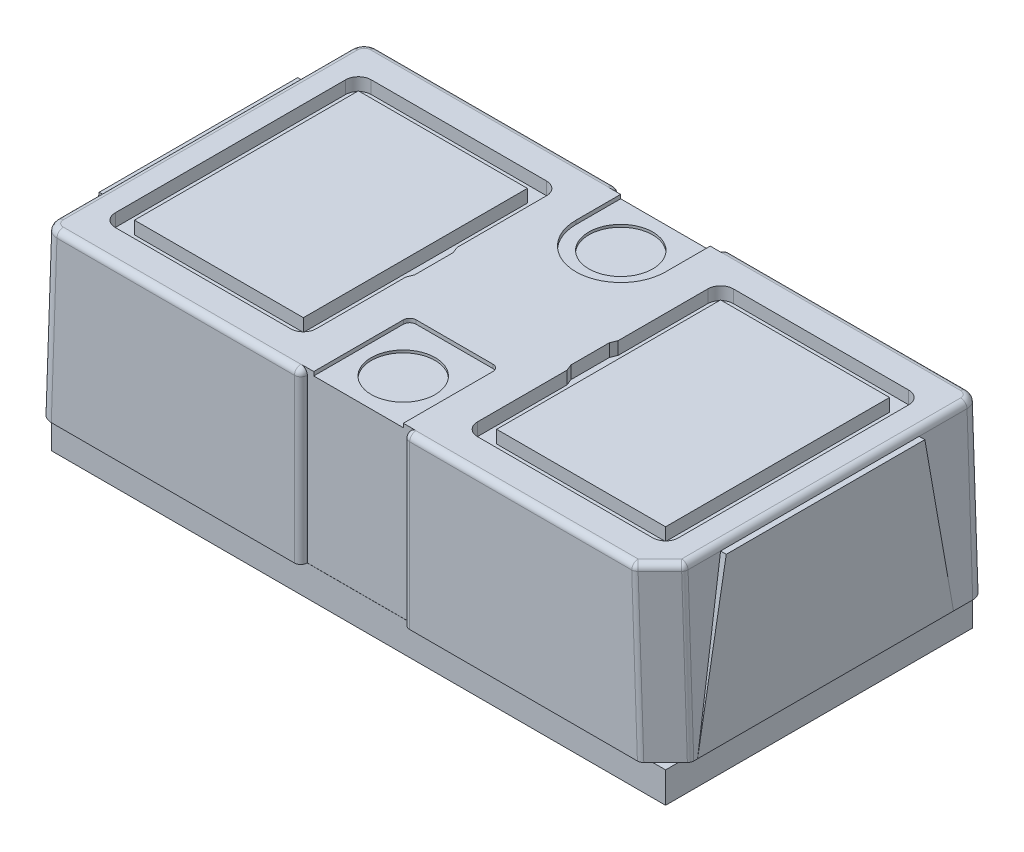
SolidWorks part; units mm, degrees
ref_plane "Front Plane" through (0, 0, 0) normal (0, 0, 1) x (1, 0, 0)
ref_plane "Top Plane" through (0, 0, 0) normal (0, 1, 0) x (1, 0, 0)
ref_plane "Right Plane" through (0, 0, 0) normal (1, 0, 0) x (0, 0, -1)
sketch "Sketch1" plane through (0, 0, 0) normal (0, 1, 0) x (1, 0, 0)
  line L1 (-2.4, -1.2) -> (2.4, -1.2)
  line L2 (-2.4, -1.2) -> (-2.4, 1.2)
  line L3 (-2.4, 1.2) -> (2.4, 1.2)
  line L4 (2.4, -1.2) -> (2.4, 1.2)
  line L5 (-2.4, -1.2) -> (2.4, 1.2) construction
  line L6 (-2.4, 1.2) -> (2.4, -1.2) construction
  point P0 (0, 0)
  dimension "D1" = 4.8
  dimension "D2" = 2.4
extrude "Boss-Extrude1" add sketch "Sketch1" along normal blind 0.24
sketch "Sketch2" plane through (0, 0, 0) normal (0, -1, 0) x (1, 0, 0)
  line L0 (-2.4, -1.2) -> (-2.4, 1.2) construction
  line L1 (-1.85, 1.05) -> (-1.35, 1.05)
  line L2 (-1.85, 1.05) -> (-1.85, 0.55)
  line L3 (-1.85, 0.55) -> (-1.35, 0.55)
  line L4 (-1.35, 1.05) -> (-1.35, 0.55)
  line L5 (-1.05, 1.05) -> (-0.55, 1.05)
  line L6 (-1.05, 1.05) -> (-1.05, 0.55)
  line L7 (-1.05, 0.55) -> (-0.55, 0.55)
  line L8 (-0.55, 1.05) -> (-0.55, 0.55)
  line L9 (-0.25, 1.05) -> (0.25, 1.05)
  line L10 (-0.25, 1.05) -> (-0.25, 0.55)
  line L11 (-0.25, 0.55) -> (0.25, 0.55)
  line L12 (0.25, 1.05) -> (0.25, 0.55)
  line L13 (0.55, 1.05) -> (1.05, 1.05)
  line L14 (0.55, 1.05) -> (0.55, 0.55)
  line L15 (0.55, 0.55) -> (1.05, 0.55)
  line L16 (1.05, 1.05) -> (1.05, 0.55)
  line L17 (1.35, 1.05) -> (1.85, 1.05)
  line L18 (1.35, 1.05) -> (1.35, 0.55)
  line L19 (1.35, 0.55) -> (1.85, 0.55)
  line L20 (1.85, 1.05) -> (1.85, 0.55)
  line L21 (-1.85, 0.25) -> (-1.35, 0.25)
  line L22 (-1.85, 0.25) -> (-1.85, -0.25)
  line L23 (-1.85, -0.25) -> (-1.35, -0.25)
  line L24 (-1.35, 0.25) -> (-1.35, -0.25)
  line L25 (-1.93, -0.55) -> (-1.35, -0.55)
  line L26 (-1.85, -0.8) -> (-1.85, -1.05)
  line L27 (-1.85, -1.05) -> (-1.35, -1.05)
  line L28 (-1.35, -0.55) -> (-1.35, -1.05)
  line L29 (-1.05, -0.55) -> (-0.55, -0.55)
  line L30 (-1.05, -0.55) -> (-1.05, -1.05)
  line L31 (-1.05, -1.05) -> (-0.55, -1.05)
  line L32 (-0.55, -0.55) -> (-0.55, -1.05)
  line L33 (-0.25, -0.55) -> (0.25, -0.55)
  line L34 (-0.25, -0.55) -> (-0.25, -1.05)
  line L35 (-0.25, -1.05) -> (0.25, -1.05)
  line L36 (0.25, -0.55) -> (0.25, -1.05)
  line L37 (0.55, -0.55) -> (1.05, -0.55)
  line L38 (0.55, -0.55) -> (0.55, -1.05)
  line L39 (0.55, -1.05) -> (1.05, -1.05)
  line L40 (1.05, -0.55) -> (1.05, -1.05)
  line L41 (1.35, -0.55) -> (1.85, -0.55)
  line L42 (1.35, -0.55) -> (1.35, -1.05)
  line L43 (1.35, -1.05) -> (1.85, -1.05)
  line L44 (1.85, -0.55) -> (1.85, -1.05)
  line L45 (1.35, 0.25) -> (1.85, 0.25)
  line L46 (1.35, 0.25) -> (1.35, -0.25)
  line L47 (1.35, -0.25) -> (1.85, -0.25)
  line L48 (1.85, 0.25) -> (1.85, -0.25)
  line L50 (2.4, -1.2) -> (-2.4, -1.2) construction
  line L52 (-1.93, -0.55) -> (-1.93, -0.8)
  line L53 (-1.93, -0.8) -> (-1.85, -0.8)
  dimension "D1" = 0.5
  dimension "D2" = 0.55
  dimension "D3" = 0.8
  dimension "D4" = 1.6
  dimension "D5" = 2.4
  dimension "D6" = 3.2
  dimension "D7" = 0.15
  dimension "D8" = 0.8
  dimension "D9" = 1.6
  dimension "D10" = 0.25
  dimension "D11" = 0.08
extrude "Boss-Extrude2" add sketch "Sketch2" along normal blind 0.01
sketch "Sketch3" plane through (0, 0.24, 0) normal (0, 1, 0) x (1, 0, 0)
  line L1 (-2.45, -1.25) -> (2.45, -1.25)
  line L2 (-2.45, -1.25) -> (-2.45, 1.25)
  line L3 (-2.45, 1.25) -> (2.45, 1.25)
  line L4 (2.45, -1.25) -> (2.45, 1.25)
  line L5 (-2.45, -1.25) -> (2.45, 1.25) construction
  line L6 (-2.45, 1.25) -> (2.45, -1.25) construction
  point P0 (0, 0)
  dimension "D1" = 4.9
  dimension "D2" = 2.5
extrude "Boss-Extrude3" add sketch "Sketch3" along normal offset from surface 1.56 draft 2
sketch "Sketch11" plane through (0, 0, 0) normal (0, 0, 1) x (1, 0, 0)
  line L4 (2.45, 0.24) -> (2.4039, 1.56)
  line L5 (2.4039, 1.56) -> (-2.4039, 1.56)
  line L6 (-2.4039, 1.56) -> (-2.45, 0.24)
  line L7 (-2.45, 0.24) -> (2.45, 0.24)
  line L8 (2.45, 0.24) -> (2.4039, 1.56)
  line L9 (2.4039, 1.56) -> (-2.4039, 1.56)
  line L10 (-2.4039, 1.56) -> (-2.45, 0.24)
  line L11 (-2.45, 0.24) -> (2.45, 0.24)
  dimension "D1" = 0
extrude "Boss-Extrude5" add sketch "Sketch11" along normal mid plane 2.5
fillet "Fillet1" radius 0.1 3 edges at (-2.427, 0.9, -1.25) (2.427, 0.9, -1.25) (-2.427, 0.9, 1.25)
sketch "Sketch5" plane through (0, 1.56, 0) normal (0, 1, 0) x (1, 0, 0)
  line L0 (2.4039, -1.25) -> (2.8092, -0.8447) construction
  line L1 (2.4039, 1.15) -> (2.4039, -1.25) construction
  point P5 (0, 0)
  point P6 (2.4039, -1.25)
  dimension "D1" = 45
ref_plane "Plane1" through (2.4039, 1.56, 1.25) normal (0.7071, 0, -0.7071) x (-0.7071, 0, -0.7071)
sketch "Sketch6" plane through (2.4039, 1.56, 1.25) normal (0.7071, 0, -0.7071) x (-0.7071, 0, -0.7071)
  line L3 (-0.0326, -1.32) -> (0, 0) construction
  line L8 (-0.0326, -1.32) -> (0, 0)
  line L9 (0.1084, -1.32) -> (0.141, 0)
  line L10 (0.1084, -1.3235) -> (0.141, -0.0035) construction
  line L11 (0, 0) -> (0.141, 0)
  line L14 (-0.0326, -1.32) -> (0.1084, -1.32)
  line L16 (0.0381, -1.32) -> (1.7352, -1.32) construction
  line L17 (1.6971, 0) -> (0, 0) construction
  point P2 (0.1033, -1.5277)
  point P9 (0.146, 0.1987)
  dimension "D1" = 0.141
extrude "Cut-Extrude2" cut sketch "Sketch6" against normal through all both and the other way through all
sketch "Sketch10" plane through (0, 0.24, 0) normal (0, -1, 0) x (1, 0, 0)
  line L13 (-2.3499, 1.25) -> (2.2505, 1.25) construction
  line L14 (-0.4, 1.25) -> (0.4, 1.25)
  line L15 (-0.4, 1.25) -> (-0.4, 1.199)
  line L16 (-0.4, 1.199) -> (0.4, 1.199)
  line L17 (0.4, 1.25) -> (0.4, 1.199)
  line L18 (2.3499, -1.25) -> (-2.3499, -1.25) construction
  line L19 (-0.4, -1.25) -> (0.4, -1.25)
  line L20 (-0.4, -1.25) -> (-0.4, -1.199)
  line L21 (-0.4, -1.199) -> (0.4, -1.199)
  line L22 (0.4, -1.25) -> (0.4, -1.199)
  line L23 (0, 1.199) -> (0, 0) construction
  line L24 (0, 0) -> (0, -1.199) construction
  dimension "D1" = 0.051
  dimension "D2" = 0.8
extrude "Cut-Extrude3" cut sketch "Sketch10" against normal through all
fillet "Fillet2" radius 0.05 24 edges at (-2.4039, 1.56, 0) (1.3519, 1.56, -1.25) (2.4039, 1.56, -0.0497) (-2.3746, 1.56, 1.2207) (2.3746, 1.56, -1.2207) (-2.3746, 1.56, -1.2207) (1.3022, 1.56, 1.25) (2.2275, 0.9, 1.25) (2.3042, 1.56, 1.1503) (2.427, 0.9, 1.0505) (-1.3519, 1.56, 1.25) (-1.3519, 1.56, -1.25) (-0.4, 1.56, 1.2245) (-0.4, 0.9, 1.25) (0.4, 1.56, 1.2245) (0.4, 0.9, 1.25) (0.4, 0.24, 1.225) (-0.4, 0.24, 1.225) (-0.4, 1.56, -1.2245) (-0.4, 0.9, -1.25) (0.4, 1.56, -1.2245) (0.4, 0.9, -1.25) (0.4, 0.24, -1.225) (-0.4, 0.24, -1.225)
sketch "Sketch9" plane through (0, 0, 0) normal (1, 0, 0) x (0, 0, -1)
  line L0 (-1, 0.24) -> (-0.7758, 1.5117)
  line L1 (-1.0298, 0.24) -> (1.15, 0.24) construction
  line L2 (1.15, 1.5117) -> (-1.0298, 1.5117) construction
  line L3 (-0.7758, 1.5117) -> (0.7758, 1.5117)
  line L4 (0.7758, 1.5117) -> (1, 0.24)
  line L5 (-1.1005, 0.24) -> (1.2, 0.24) construction
  line L6 (1, 0.24) -> (-1, 0.24)
  point P10 (0, 0.24)
  point P12 (0, 1.5117)
  dimension "D1" = 20
  dimension "D2" = 2
extrude "Boss-Extrude4" add sketch "Sketch9" along normal mid plane 4.9
sketch "Sketch12" plane through (0, 1.56, 0) normal (0, 1, 0) x (1, 0, 0)
  line L0 (-0.4, -1.199) -> (0.4, -1.199) construction
  line L1 (-0.35, -1.199) -> (0.35, -1.199)
  line L2 (-0.35, -1.199) -> (-0.35, -0.499)
  line L3 (-0.3, -0.449) -> (0.3, -0.449)
  line L4 (0.35, -1.199) -> (0.35, -0.499)
  line L5 (0.45, 1.199) -> (-0.45, 1.199) construction
  line L6 (-0.35, 1.199) -> (0.35, 1.199)
  line L7 (-0.35, 1.199) -> (-0.35, 0.85)
  line L9 (0.35, 1.199) -> (0.35, 0.85)
  line L10 (-0.45, -1.25) -> (-2.3056, -1.25) construction
  line L11 (0, 1.199) -> (0, 0.5) construction
  arc A0 (-0.35, 0.85) -> (0.35, 0.85) centre (0, 0.85) ccw
  arc A1 (0.3, -0.449) -> (0.35, -0.499) centre (0.3, -0.499) cw
  arc A2 (-0.35, -0.499) -> (-0.3, -0.449) centre (-0.3, -0.499) cw
  point P15 (0, 1.199)
  point P16 (0, -1.199)
  dimension "D4" = 0.05
  dimension "D1" = 0.7
  dimension "D2" = 0.75
  dimension "D3" = 2.1
extrude "Cut-Extrude4" cut sketch "Sketch12" against normal blind 0.03
sketch "Sketch13" plane through (0, 1.56, 0) normal (0, 1, 0) x (1, 0, 0)
  line L1 (0, 0.85) -> (0, 0) construction
  line L2 (0, 0) -> (0, -0.85) construction
  circle A0 centre (0, 0.85) radius 0.25
  circle A1 centre (0, -0.85) radius 0.25
  dimension "D1" = 0.5
extrude "Cut-Extrude5" cut sketch "Sketch13" against normal blind 0.05
sketch "Sketch15" plane through (0, 1.56, 0) normal (0, 1, 0) x (1, 0, 0)
  line L0 (-0.61, 0) -> (0, 0) construction
  line L1 (-2.1, 1) -> (-0.73, 1)
  line L2 (-2.2, 0.9) -> (-2.2, -0.9)
  line L3 (-2.1, -1) -> (-0.73, -1)
  line L4 (-0.63, 0.9) -> (-0.63, 0.2)
  line L5 (0.73, 1) -> (2.1, 1)
  line L6 (0.63, 0.9) -> (0.63, 0.2)
  line L7 (0.73, -1) -> (2.1, -1)
  line L8 (2.2, 0.9) -> (2.2, -0.9)
  line L9 (0, 0) -> (0.61, 0) construction
  line L10 (-2.45, 0.7758) -> (-2.45, -0.7758) construction
  line L11 (-0.45, -1.25) -> (-2.3056, -1.25) construction
  line L12 (-2.075, 0.875) -> (-2.075, -0.875)
  line L17 (-2.075, -0.875) -> (-0.755, -0.875)
  line L18 (-0.755, 0.875) -> (-0.755, -0.875)
  line L19 (-2.075, 0.875) -> (-0.755, 0.875)
  line L20 (0.755, 0.875) -> (0.755, -0.875)
  line L21 (0.755, -0.875) -> (2.075, -0.875)
  line L22 (2.075, 0.875) -> (2.075, -0.875)
  line L23 (0.755, 0.875) -> (2.075, 0.875)
  line L24 (0.63, 1) -> (0.63, -1) construction
  line L25 (0.63, -1) -> (2.2, -1) construction
  line L26 (2.2, 1) -> (2.2, -1) construction
  line L27 (0.63, 1) -> (2.2, 1) construction
  line L28 (-2.2, 1) -> (-0.63, 1) construction
  line L29 (-0.63, 1) -> (-0.63, -1) construction
  line L30 (-2.2, 1) -> (-2.2, -1) construction
  line L31 (-2.2, -1) -> (-0.63, -1) construction
  line L32 (-0.63, 0.2) -> (-0.61, 0.15)
  line L33 (-0.61, 0.15) -> (-0.61, -0.15)
  line L34 (-0.61, -0.15) -> (-0.63, -0.2)
  line L35 (-0.63, -0.2) -> (-0.63, -0.9)
  line L36 (0.63, 0.2) -> (0.61, 0.15)
  line L37 (0.61, 0.15) -> (0.61, -0.15)
  line L38 (0.61, -0.15) -> (0.63, -0.2)
  line L39 (0.63, -0.2) -> (0.63, -0.9)
  arc A0 (0.63, -0.9) -> (0.73, -1) centre (0.73, -0.9) ccw
  arc A1 (2.1, -1) -> (2.2, -0.9) centre (2.1, -0.9) ccw
  arc A2 (2.1, 1) -> (2.2, 0.9) centre (2.1, 0.9) cw
  arc A3 (0.73, 1) -> (0.63, 0.9) centre (0.73, 0.9) ccw
  arc A4 (-0.73, 1) -> (-0.63, 0.9) centre (-0.73, 0.9) cw
  arc A5 (-2.1, 1) -> (-2.2, 0.9) centre (-2.1, 0.9) ccw
  arc A6 (-0.73, -1) -> (-0.63, -0.9) centre (-0.73, -0.9) ccw
  arc A7 (-2.2, -0.9) -> (-2.1, -1) centre (-2.1, -0.9) ccw
  point P50 (0, 0)
  point P57 (0, 0)
  point P58 (0, 0)
  point P59 (0, 0)
  point P60 (-0.61, 0)
  point P61 (0, 0)
  point P62 (0.61, 0)
  point P63 (0, 0)
  point P64 (-0.73, 0.8438)
  dimension "D5" = 0.1
  dimension "D1" = 0.25
  dimension "D2" = 1.82
  dimension "D3" = 0.25
  dimension "D4" = 0.125
  dimension "D6" = 0.02
  dimension "D7" = 0.3
  dimension "D8" = 0.4
extrude "Cut-Extrude6" cut sketch "Sketch15" against normal blind 0.1
